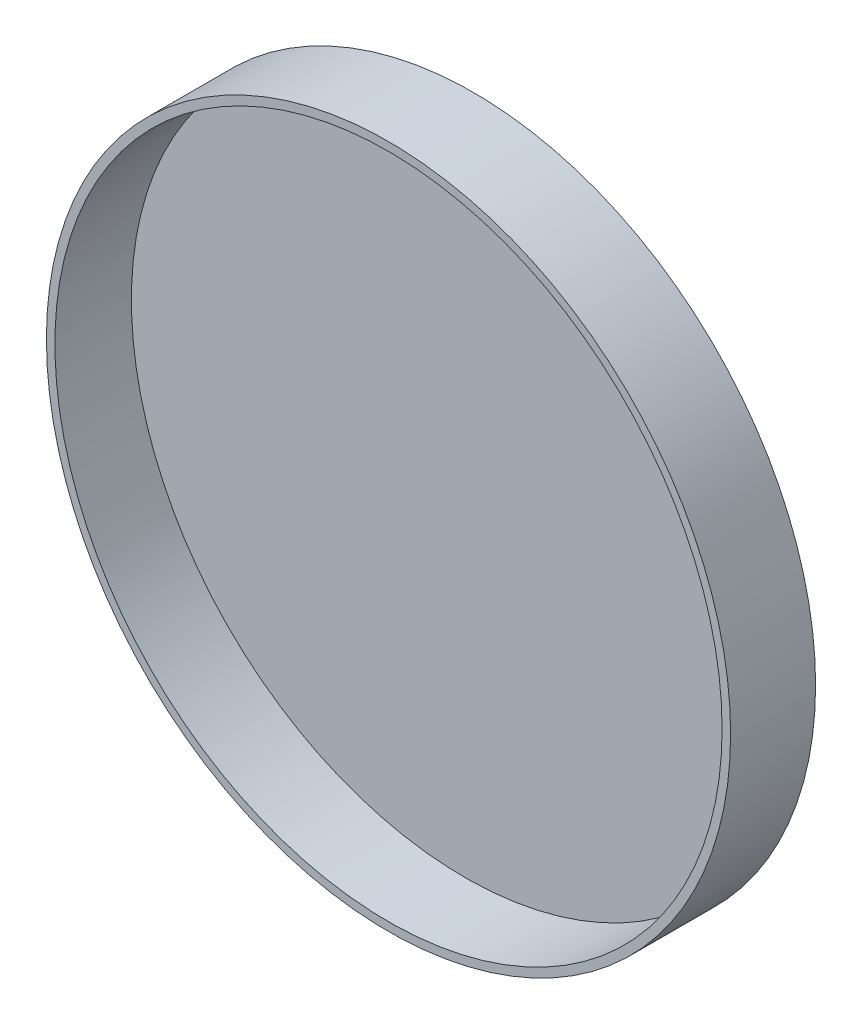
SolidWorks part; units mm, degrees
ref_plane "Plan de face" through (0, 0, 0) normal (0, 0, 1) x (1, 0, 0)
ref_plane "Plan de dessus" through (0, 0, 0) normal (0, 1, 0) x (1, 0, 0)
ref_plane "Plan de droite" through (0, 0, 0) normal (1, 0, 0) x (0, 0, -1)
sketch "Esquisse1" plane through (0, 0, 0) normal (0, 0, 1) x (1, 0, 0)
  circle A0 centre (0, 0) radius 40.25
  dimension "D1" = 80.5
extrude "Boss.-Extru.1" add sketch "Esquisse1" along normal blind 1
sketch "Esquisse2" plane through (0, 0, 1) normal (0, 0, 1) x (1, 0, 0)
  circle A0 centre (0, 0) radius 40.25
  circle A1 centre (0, 0) radius 39.25
  circle A2 centre (0, 0) radius 40.25 construction
  dimension "D1" = 1
extrude "Boss.-Extru.2" add sketch "Esquisse2" along normal blind 9
